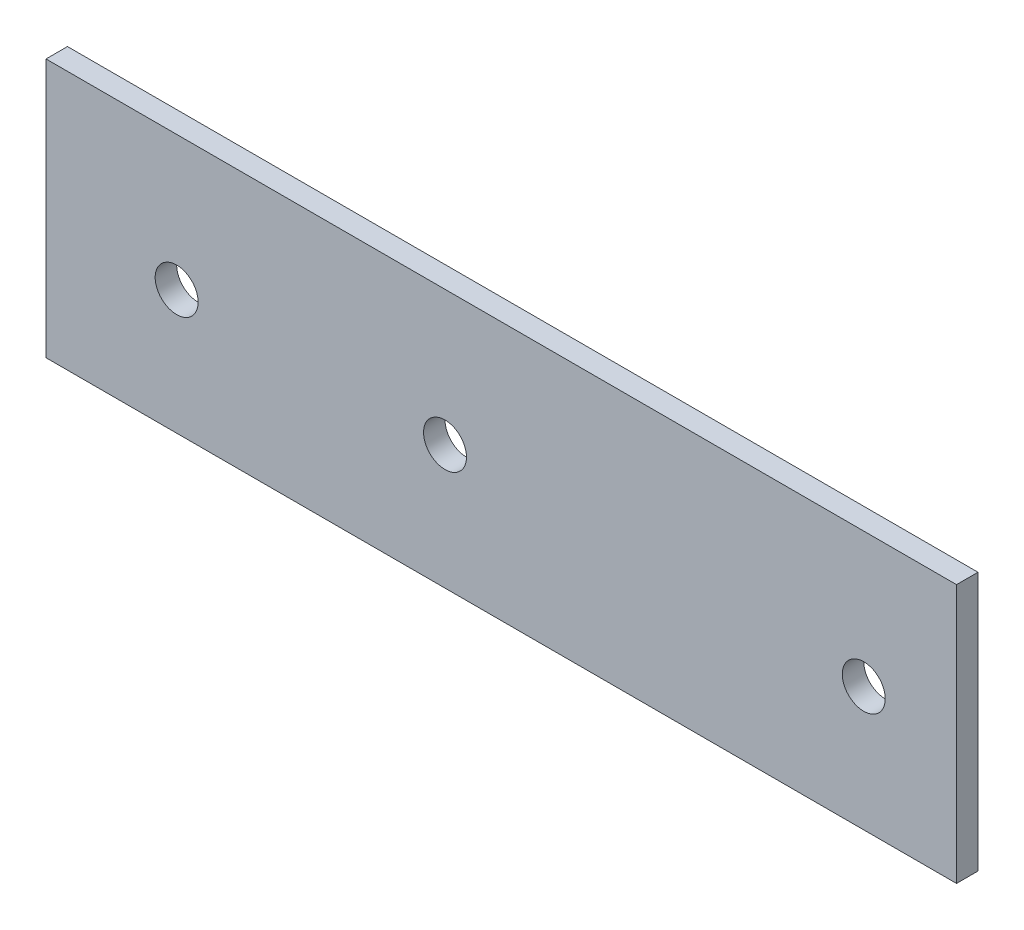
SolidWorks part; units mm, degrees
ref_plane "Front Plane" through (0, 0, 0) normal (0, 0, 1) x (1, 0, 0)
ref_plane "Top Plane" through (0, 0, 0) normal (0, 1, 0) x (1, 0, 0)
ref_plane "Right Plane" through (0, 0, 0) normal (1, 0, 0) x (0, 0, -1)
sketch "Sketch1" plane through (0, 0, 0) normal (0, 0, 1) x (1, 0, 0)
  line L1 (-44.718, 19.9046) -> (89.9153, 19.9046)
  line L2 (-44.718, 19.9046) -> (-44.718, -18.3616)
  line L3 (-44.718, -18.3616) -> (89.9153, -18.3616)
  line L4 (89.9153, 19.9046) -> (89.9153, -18.3616)
  circle A0 centre (-25.4, 0) radius 3.175
  circle A1 centre (76.2, 0) radius 3.175
  circle A2 centre (14.2807, 0) radius 3.175
extrude "Boss-Extrude1" add sketch "Sketch1" along normal blind 3.175
